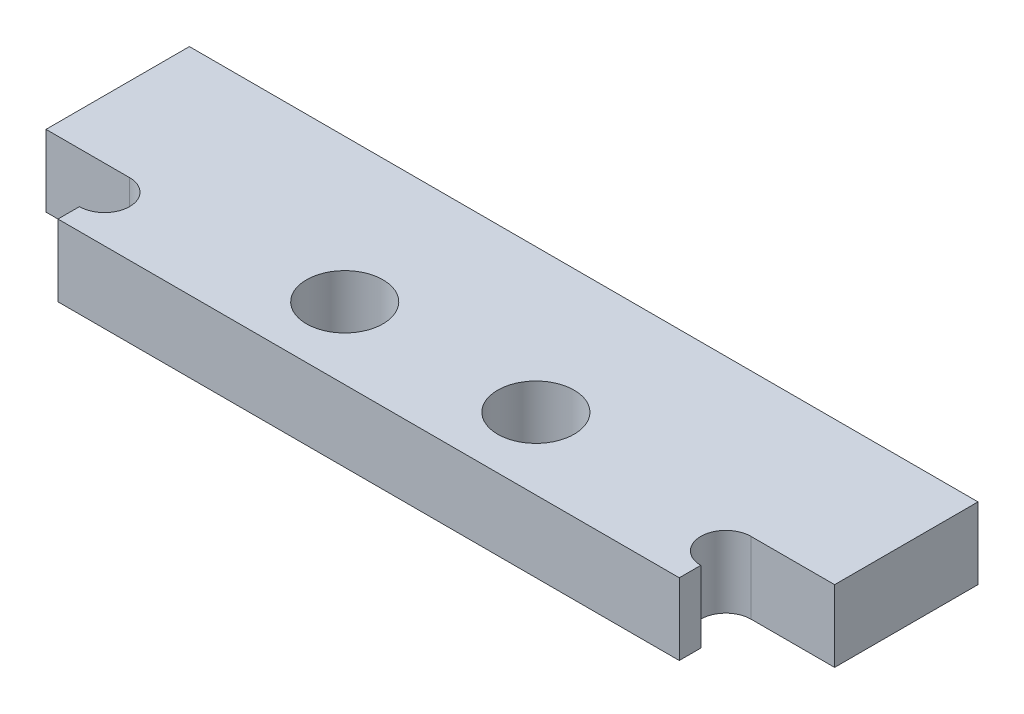
SolidWorks part; units mm, degrees
material "Thornel Mat VMA"
ref_plane "前视基准面" through (0, 0, 0) normal (0, 0, 1) x (1, 0, 0)
ref_plane "上视基准面" through (0, 0, 0) normal (0, 1, 0) x (1, 0, 0)
ref_plane "右视基准面" through (0, 0, 0) normal (1, 0, 0) x (0, 0, -1)
sketch "草图1" plane through (0, 0, 0) normal (0, 1, 0) x (1, 0, 0)
  line L0 (0, 0) -> (0, -3.5683) construction
  line L1 (13, -6) -> (-13, -6)
  line L2 (13, -6) -> (13, -3)
  line L3 (13, 6) -> (-13, 6)
  line L4 (-13, -6) -> (-13, -3)
  line L5 (13, -6) -> (-13, 6) construction
  line L6 (13, 6) -> (-13, -6) construction
  line L7 (-13, -3) -> (-16.5, -3)
  line L8 (-16.5, -3) -> (-16.5, 3)
  line L9 (-16.5, 3) -> (-13, 3)
  line L10 (-13, 3) -> (-13, 6)
  line L11 (13, -3) -> (16.5, -3)
  line L12 (16.5, -3) -> (16.5, 3)
  line L13 (16.5, 3) -> (13, 3)
  line L14 (13, 3) -> (13, 6)
  line L15 (-13, 3) -> (13, 3)
  circle A0 centre (-4, -3) radius 1.6
  circle A1 centre (4, -3) radius 1.6
  circle A3 centre (-13, -4.05) radius 1.05
  circle A5 centre (-13, 4.05) radius 1.05
  circle A6 centre (13, -4.05) radius 1.05
  circle A7 centre (13, 4.05) radius 1.05
  point P0 (0, 0)
  dimension "D4" = 3.2
  dimension "D9" = 2.1
  dimension "D1" = 12
  dimension "D2" = 26
  dimension "D3" = 8
  dimension "D5" = 3
  dimension "D6" = 6
  dimension "D7" = 3.5
  dimension "D8" = 3
extrude "凸台-拉伸1" add sketch "草图1" along normal blind 3 contours L13 A7 L14 L3 L10 A5 L9 L8 L7 A3 L4 L1 L2 A6 L11 L12 A0 A1
